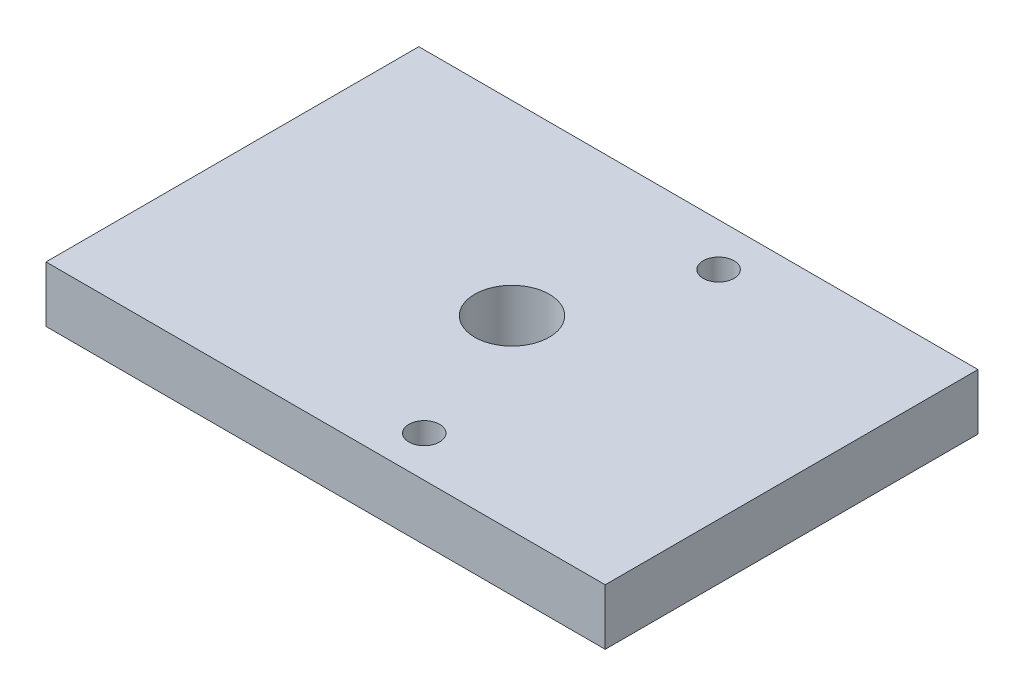
SolidWorks part; units mm, degrees
ref_plane "Front Plane" through (0, 0, 0) normal (0, 0, 1) x (1, 0, 0)
ref_plane "Top Plane" through (0, 0, 0) normal (0, 1, 0) x (1, 0, 0)
ref_plane "Right Plane" through (0, 0, 0) normal (1, 0, 0) x (0, 0, -1)
sketch "Sketch1" plane through (0, 0, 0) normal (0, 1, 0) x (1, 0, 0)
  line L1 (-30, 20) -> (30, 20)
  line L2 (-30, 20) -> (-30, -20)
  line L3 (-30, -20) -> (30, -20)
  line L4 (30, 20) -> (30, -20)
  line L5 (-30, 20) -> (30, -20) construction
  line L6 (-30, -20) -> (30, 20) construction
  circle A0 centre (0, 0) radius 4
  point P0 (0, 0)
  dimension "D3" = 8
  dimension "D1" = 60
  dimension "D2" = 40
extrude "Boss-Extrude1" add sketch "Sketch1" along normal blind 6
sketch "Sketch2" plane through (0, 6, 0) normal (0, 1, 0) x (1, 0, 0)
  circle A0 centre (6.7951, 15.3729) radius 1.65
  circle A1 centre (6.2025, -15.6214) radius 1.65
  dimension "D1" = 3.3
  dimension "D2" = 3.3
extrude "Cut-Extrude1" cut sketch "Sketch2" against normal blind 10
